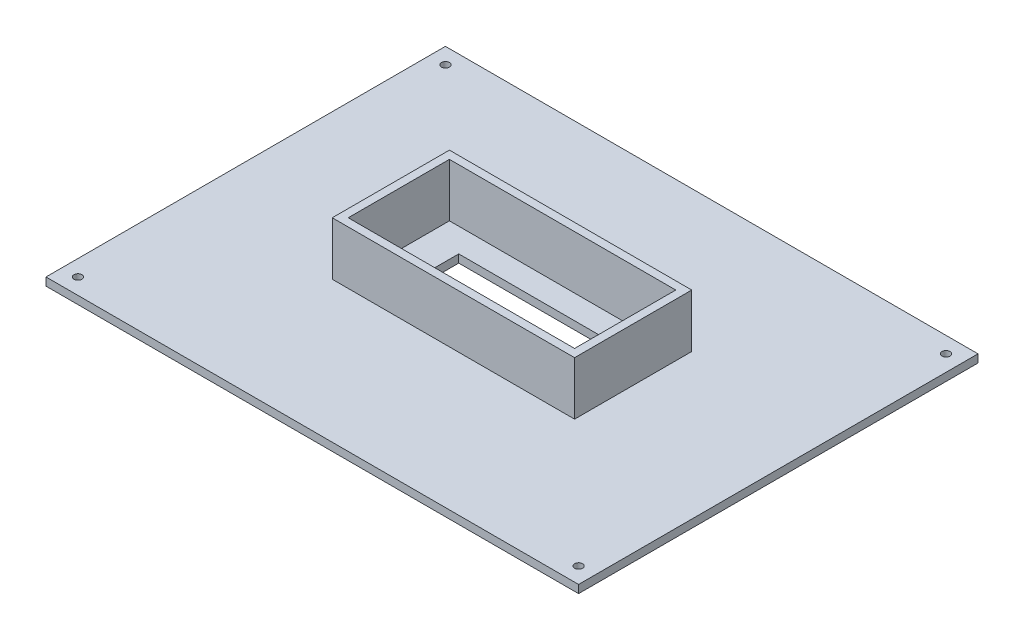
SolidWorks part; units mm, degrees
ref_plane "Front Plane" through (0, 0, 0) normal (0, 0, 1) x (1, 0, 0)
ref_plane "Top Plane" through (0, 0, 0) normal (0, 1, 0) x (1, 0, 0)
ref_plane "Right Plane" through (0, 0, 0) normal (1, 0, 0) x (0, 0, -1)
sketch "Sketch1" plane through (0, 0, 0) normal (0, 1, 0) x (1, 0, 0)
  line L1 (-100, 75) -> (100, 75)
  line L2 (-100, 75) -> (-100, -75)
  line L3 (-100, -75) -> (100, -75)
  line L4 (100, 75) -> (100, -75)
  line L5 (-100, 75) -> (100, -75) construction
  line L6 (-100, -75) -> (100, 75) construction
  point P0 (0, 0)
  dimension "D1" = 200
  dimension "D2" = 150
extrude "Boss-Extrude1" add sketch "Sketch1" along normal blind 3
sketch "Sketch2" plane through (0, 3, 0) normal (0, 1, 0) x (1, 0, 0)
  line L0 (100, -75) -> (100, 75) construction
  line L1 (-100, -75) -> (100, -75) construction
  line L2 (-100, 0) -> (100, 0) construction
  line L3 (-100, 75) -> (-100, -75) construction
  line L4 (0, 75) -> (0, -75) construction
  line L5 (100, 75) -> (-100, 75) construction
  circle A0 centre (94, -69) radius 1.5
  circle A1 centre (94, 69) radius 1.5
  circle A2 centre (-94, -69) radius 1.5
  circle A3 centre (-94, 69) radius 1.5
  dimension "D3" = 3
  dimension "D1" = 6
  dimension "D2" = 6
extrude "Cut-Extrude1" cut sketch "Sketch2" against normal through all
sketch "Sketch3" plane through (0, 3, 0) normal (0, 1, 0) x (1, 0, 0)
  line L0 (0, 75) -> (0, -75) construction
  line L1 (100, 75) -> (-100, 75) construction
  line L2 (-100, -75) -> (100, -75) construction
  line L4 (-30, 10) -> (30, 10)
  line L5 (-30, 10) -> (-30, -10)
  line L6 (-30, -10) -> (30, -10)
  line L7 (30, 10) -> (30, -10)
  line L8 (-30, 10) -> (30, -10) construction
  line L9 (-30, -10) -> (30, 10) construction
  point P6 (0, 0)
  dimension "60" = 60
  dimension "D2" = 20
extrude "Cut-Extrude2" cut sketch "Sketch3" against normal through all
sketch "Sketch4" plane through (0, 3, 0) normal (0, 1, 0) x (1, 0, 0)
  line L1 (-42.5, 19) -> (42.5, 19)
  line L2 (-42.5, 19) -> (-42.5, -19)
  line L3 (-42.5, -19) -> (42.5, -19)
  line L4 (42.5, 19) -> (42.5, -19)
  line L5 (-42.5, 19) -> (42.5, -19) construction
  line L6 (-42.5, -19) -> (42.5, 19) construction
  line L10 (-45.5, 22) -> (45.5, 22)
  line L11 (45.5, 22) -> (45.5, -22)
  line L12 (-45.5, -22) -> (45.5, -22)
  line L13 (-45.5, 22) -> (-45.5, -22)
  point P0 (0, 0)
  dimension "D1" = 85
  dimension "D2" = 38
  dimension "D3" = 3
extrude "Boss-Extrude2" add sketch "Sketch4" along normal blind 20
